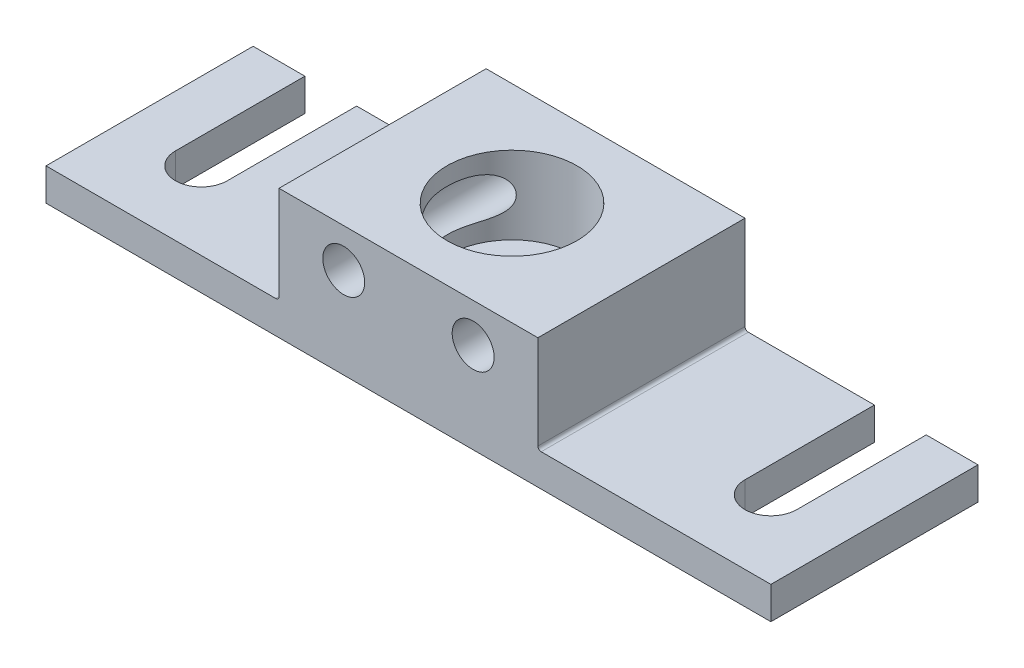
SolidWorks part; units mm, degrees
material "5052-H36"
ref_plane "Front Plane" through (0, 0, 0) normal (0, 0, 1) x (1, 0, 0)
ref_plane "Top Plane" through (0, 0, 0) normal (0, 1, 0) x (1, 0, 0)
ref_plane "Right Plane" through (0, 0, 0) normal (1, 0, 0) x (0, 0, -1)
sketch "Sketch1" plane through (0, 0, 0) normal (0, 1, 0) x (1, 0, 0)
  line L1 (-14, -4) -> (14, -4)
  line L2 (-14, -4) -> (-14, 4)
  line L3 (-14, 4) -> (14, 4)
  line L4 (14, -4) -> (14, 4)
  line L5 (-14, -4) -> (14, 4) construction
  line L6 (-14, 4) -> (14, -4) construction
  point P0 (0, 0)
  dimension "D1" = 8
  dimension "D2" = 28
extrude "Boss-Extrude1" add sketch "Sketch1" along normal blind 1.25
sketch "Sketch2" plane through (0, 1.25, 0) normal (0, 1, 0) x (1, 0, 0)
  line L0 (14, 4) -> (-14, 4) construction
  line L1 (-5, -4) -> (5, -4)
  line L2 (-5, -4) -> (-5, 4)
  line L3 (-5, 4) -> (5, 4)
  line L4 (5, -4) -> (5, 4)
  line L5 (-5, -4) -> (5, 4) construction
  line L6 (-5, 4) -> (5, -4) construction
  point P0 (0, 0)
  dimension "D1" = 10
  dimension "D2" = 8
extrude "Boss-Extrude2" add sketch "Sketch2" along normal blind 3.75
sketch "Sketch3" plane through (0, 5, 0) normal (0, 1, 0) x (1, 0, 0)
  circle A0 centre (0, 0) radius 2.51
extrude "Cut-Extrude1" cut sketch "Sketch3" against normal blind 3
sketch "Sketch4" plane through (0, 2, 0) normal (0, 1, 0) x (1, 0, 0)
  line L0 (1.5, 1.15) -> (1.5, -1.15)
  line L1 (-1.5, -1.15) -> (1.5, -1.15)
  line L3 (-1.5, 1.15) -> (1.5, 1.15)
  line L5 (-1.5, -1.15) -> (1.5, 1.15) construction
  line L6 (-1.5, 1.15) -> (1.5, -1.15) construction
  line L7 (-1.5, 1.15) -> (-1.5, -1.15)
  point P0 (0, 0)
  dimension "D1" = 3
  dimension "D2" = 2.3
extrude "Cut-Extrude2" cut sketch "Sketch4" against normal through all
sketch "Sketch6" plane through (0, 1.25, 0) normal (0, 1, 0) x (1, 0, 0)
  line L0 (14, 0) -> (12, 0) construction
  line L1 (14, -4) -> (14, 4) construction
  line L2 (12, 4) -> (12, -1)
  line L3 (14, 4) -> (5, 4) construction
  line L4 (12, 4) -> (10, 4)
  line L5 (10, 4) -> (10, -1)
  line L6 (-14, 0) -> (-12, 0) construction
  line L7 (-14, 4) -> (-14, -4) construction
  line L8 (-12, 4) -> (-12, -1)
  line L9 (-5, 4) -> (-14, 4) construction
  line L10 (-12, 4) -> (-10, 4)
  line L11 (-10, 4) -> (-10, -1)
  arc A0 (10, -1) -> (12, -1) centre (11, -1) ccw
  arc A1 (-12, -1) -> (-10, -1) centre (-11, -1) ccw
extrude "Cut-Extrude4" cut sketch "Sketch6" against normal through all
sketch "Sketch7" plane through (0, 0, -4) normal (0, 0, -1) x (-1, 0, 0)
  line L0 (5, 5) -> (5, 3.5) construction
  line L1 (5, 5) -> (5, 1.25) construction
  line L2 (5, 3.5) -> (2.5, 3.5) construction
  circle A0 centre (2.5, 3.5) radius 0.81
extrude "Cut-Extrude5" cut sketch "Sketch7" against normal through all
ref_plane "Plane1" through (0, 0, 0) normal (-1, 0, 0) x (0, 0, 1)
mirror "Mirror1" about plane through (0, 0, 0) normal (-1, 0, 0) of "Cut-Extrude5"
fillet "Fillet1" radius 0.5 4 edges at (1.5, 1, 1.15) (-1.5, 1, 1.15) (1.5, 1, -1.15) (-1.5, 1, -1.15)
fillet "Fillet2" radius 0.127 2 edges at (5, 1.25, 0) (-5, 1.25, 0)
